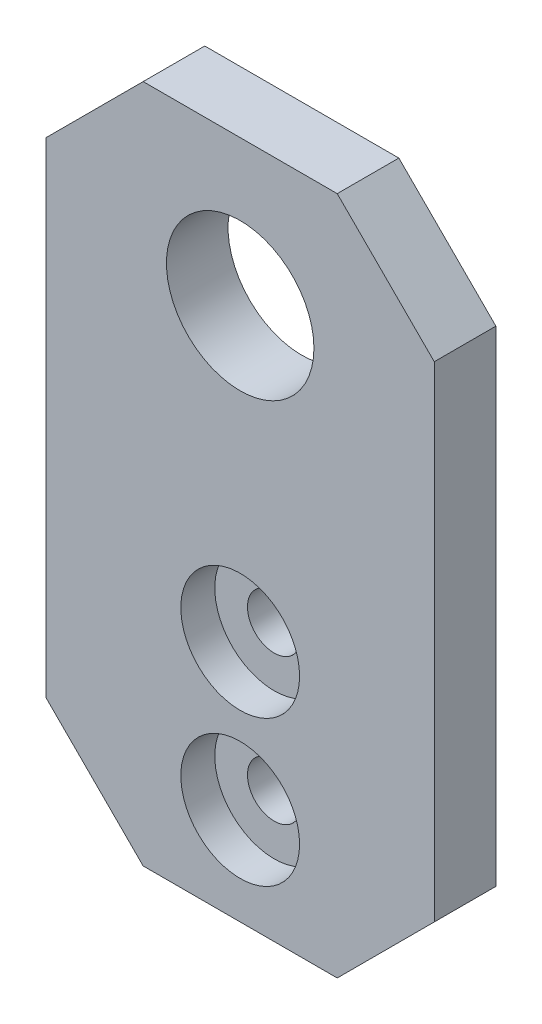
SolidWorks part; units mm, degrees
material "6061 Alloy"
ref_plane "Front Plane" through (0, 0, 0) normal (0, 0, 1) x (1, 0, 0)
ref_plane "Top Plane" through (0, 0, 0) normal (0, 1, 0) x (1, 0, 0)
ref_plane "Right Plane" through (0, 0, 0) normal (1, 0, 0) x (0, 0, -1)
sketch "Sketch1" plane through (0, 0, 0) normal (0, 0, 1) x (1, 0, 0)
  line L0 (0, 35) -> (0, -35) construction
  line L1 (-20, -35) -> (20, -35)
  line L2 (-20, -35) -> (-20, 35)
  line L3 (-20, 35) -> (20, 35)
  line L4 (20, -35) -> (20, 35)
  line L5 (-20, -35) -> (20, 35) construction
  line L6 (-20, 35) -> (20, -35) construction
  circle A0 centre (0, 20) radius 7.6
  circle A1 centre (0, -10) radius 2.5 construction
  circle A2 centre (0, -25) radius 2.5 construction
  point P4 (0, 0)
  dimension "D3" = 15.2
  dimension "D4" = 5
  dimension "D5" = 5
  dimension "D1" = 40
  dimension "D2" = 70
  dimension "D6" = 10
  dimension "D7" = 15
  dimension "D8" = 55
extrude "Boss-Extrude1" add sketch "Sketch1" along normal blind 6.35
hole_wizard "CBORE for M5 Hex Head Bolt1" positions "Sketch4" profile "Sketch5" counterbore size "M5" standard "ISO" end condition through all
sketch "Sketch4" plane through (0, 0, 6.35) normal (0, 0, 1) x (1, 0, 0)
  point P0 (0, -10)
  point P3 (0, -25)
sketch "Sketch5" plane through (0, -10, 6.35) normal (1, 0, 0) x (0, -1, 0)
  line L0 (0, 0) -> (0, 6.35)
  line L1 (0, 6.35) -> (2.75, 6.35)
  line L3 (2.75, 6.35) -> (2.75, 3.5)
  line L4 (2.75, 3.5) -> (6.119, 3.5)
  line L5 (6.119, 3.5) -> (6.119, 0)
  line L7 (6.119, 0) -> (0, 0)
  line L11 (0, -6.35) -> (0, 107.95) construction
  dimension "Thru Hole Dia." = 5.5
  dimension "Thru Hole Depth" = 6.35
  dimension "C'Bore Dia." = 12.238
  dimension "C'Bore Depth" = 3.5
chamfer "Chamfer1" distance 10 angle 45 4 edges at (20, -35, 3.175) (-20, -35, 3.175) (20, 35, 3.175) (-20, 35, 3.175)
